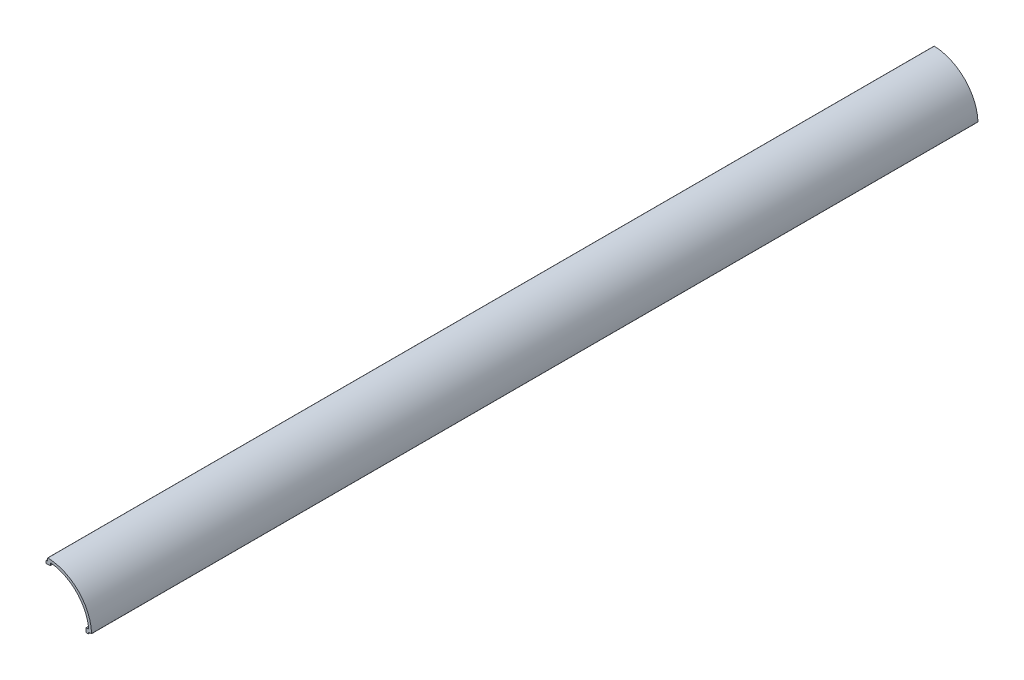
SolidWorks part; units mm, degrees
material "Nylon 101"
ref_plane "Front Plane" through (0, 0, 0) normal (0, 0, 1) x (1, 0, 0)
ref_plane "Top Plane" through (0, 0, 0) normal (0, 1, 0) x (1, 0, 0)
ref_plane "Right Plane" through (0, 0, 0) normal (1, 0, 0) x (0, 0, -1)
sketch "Sketch1" plane through (0, 0, 0) normal (0, 0, 1) x (1, 0, 0)
  line L0 (0, 0) -> (0, 13.9666) construction
  line L1 (13.9666, 1) -> (14.9666, 1)
  line L2 (0, 13.9666) -> (1, 13.9666)
  line L3 (1, 13.9666) -> (1, 14.9666)
  line L4 (0, 0) -> (10.9602, 10.9602) construction
  line L5 (13.9666, 0) -> (13.9666, 1)
  arc A0 (14.9666, 1) -> (1, 14.9666) centre (0, 0) ccw
  point P9 (0, 0)
  point P10 (0, 0)
  dimension "D1" = 15
  dimension "D2" = 1
  dimension "D3" = 1
  dimension "D4" = 45
extrude "Extrude-Thin1" add sketch "Sketch1" along normal mid plane 300 thin contours L5 L1 A0 L3 L2 thin type mid plane wall 0.9
fillet "Fillet1" radius 0.1 12 edges at (15.4402, 0.55, 0) (14.4166, 0.55, 0) (14.4166, 0, 0) (13.5166, 0, 0) (0.55, 15.4402, 0) (0, 13.5166, 0) (0, 14.4166, 0) (0.55, 14.4166, 0) (1.45, 13.5166, 0) (1.45, 14.4776, 0) (14.4776, 1.45, 0) (13.5166, 1.45, 0)
